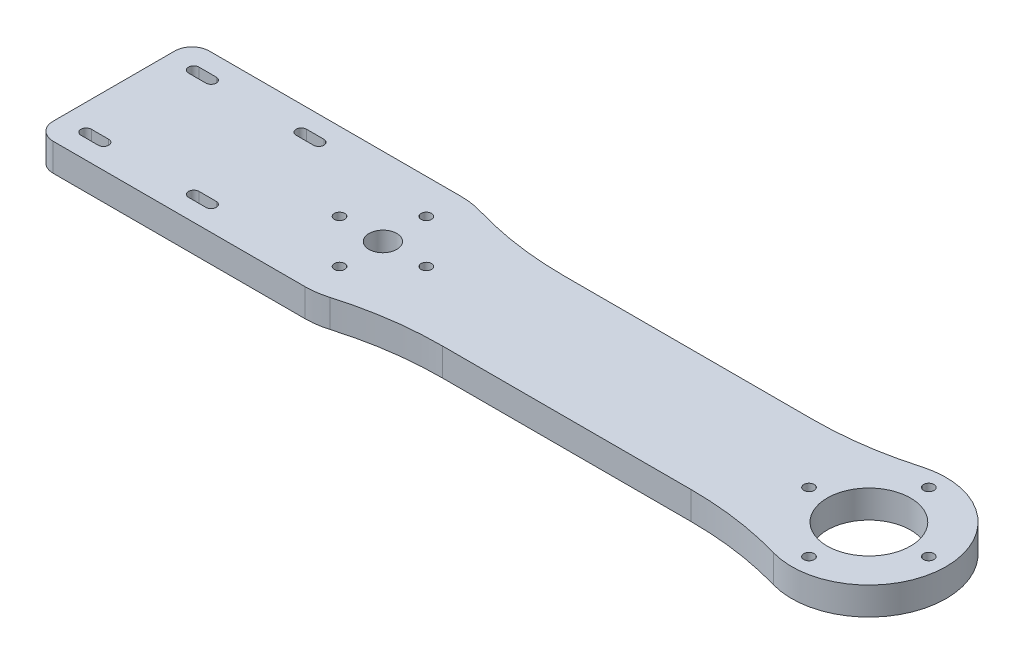
SolidWorks part; units mm, degrees
material "Pine"
ref_plane "Front Plane" through (0, 0, 0) normal (0, 0, 1) x (1, 0, 0)
ref_plane "Top Plane" through (0, 0, 0) normal (0, 1, 0) x (1, 0, 0)
ref_plane "Right Plane" through (0, 0, 0) normal (1, 0, 0) x (0, 0, -1)
sketch "Sketch1" plane through (0, 0, 0) normal (0, 1, 0) x (1, 0, 0)
  line L0 (0, 0) -> (140, 0) construction
  line L2 (0, 17.5) -> (140, 17.5)
  line L3 (0, -17.5) -> (140, -17.5)
  arc A0 (0, 17.5) -> (0, -17.5) centre (0, 0) ccw
  arc A1 (140, -17.5) -> (140, 17.5) centre (140, 0) ccw
  circle A2 centre (140, 0) radius 4
  circle A3 centre (0, 0) radius 4
  circle A4 centre (140, 0) radius 22.25
  circle A5 centre (0, 0) radius 20
  circle A6 centre (140, 0) radius 17.25
  point P5 (70, 0)
  dimension "D2" = 17.5
  dimension "D3" = 8
  dimension "D4" = 8
  dimension "D5" = 5
  dimension "D6" = 40
  dimension "D7" = 34.5
  dimension "D1" = 140
extrude "Boss-Extrude1" add sketch "Sketch1" along normal blind 8
sketch "Sketch2" plane through (0, 8, 0) normal (0, 1, 0) x (1, 0, 0)
  line L0 (0, 0) -> (-65, 0)
  line L1 (0, 0) -> (-65, 0) construction
  line L2 (0, -22.5) -> (-65, -22.5)
  line L3 (0, 22.5) -> (-65, 22.5)
  line L4 (-32.5, 0) -> (-65, 0)
  line L5 (-65, 0) -> (-65, 15.5)
  line L6 (-65, 15.5) -> (-70, 15.5) construction
  line L7 (-34, 15.5) -> (-39, 15.5) construction
  line L8 (-65, 14) -> (-70, 14)
  line L9 (-65, 17) -> (-70, 17)
  line L10 (-65, 22.5) -> (-77.5, 22.5)
  line L11 (-65, 22.5) -> (-65, -22.5)
  line L12 (-65, -22.5) -> (-77.5, -22.5)
  line L13 (-77.5, 22.5) -> (-77.5, -22.5)
  line L14 (-34, 14) -> (-39, 14)
  line L15 (-34, 17) -> (-39, 17)
  line L16 (-34, -15.5) -> (-39, -15.5) construction
  line L17 (-34, -17) -> (-39, -17)
  line L18 (-34, -14) -> (-39, -14)
  line L19 (-65, -15.5) -> (-70, -15.5) construction
  line L20 (-65, -17) -> (-70, -17)
  line L21 (-65, -14) -> (-70, -14)
  line L22 (-67.5, 15.5) -> (-36.5, -15.5)
  line L23 (-54.5, 0) -> (-49.5, 0) construction
  line L25 (-54.5, 11) -> (-49.5, 11)
  line L26 (-54.5, -11) -> (-49.5, -11)
  arc A0 (0, -22.5) -> (0, 22.5) centre (0, 0) ccw
  arc A1 (-65, 22.5) -> (-65, -22.5) centre (-65, 0) ccw
  circle A2 centre (0, 0) radius 4
  arc A3 (-65, 14) -> (-65, 17) centre (-65, 15.5) ccw
  arc A4 (-70, 17) -> (-70, 14) centre (-70, 15.5) ccw
  arc A5 (-34, 14) -> (-34, 17) centre (-34, 15.5) ccw
  arc A6 (-39, 17) -> (-39, 14) centre (-39, 15.5) ccw
  arc A7 (-34, -17) -> (-34, -14) centre (-34, -15.5) ccw
  arc A8 (-39, -14) -> (-39, -17) centre (-39, -15.5) ccw
  arc A9 (-65, -17) -> (-65, -14) centre (-65, -15.5) ccw
  arc A10 (-70, -14) -> (-70, -17) centre (-70, -15.5) ccw
  arc A11 (-54.5, 11) -> (-54.5, -11) centre (-54.5, 0) ccw
  arc A12 (-49.5, -11) -> (-49.5, 11) centre (-49.5, 0) ccw
  point P3 (-32.5, 0)
  point P16 (-67.5, 15.5)
  point P28 (-36.5, 15.5)
  point P35 (-36.5, -15.5)
  point P42 (-67.5, -15.5)
  point P50 (-52, 0)
  dimension "D2" = 22.5
  dimension "D3" = 65
  dimension "D1" = 65
  dimension "D4" = 12.5
  dimension "D5" = 2
  dimension "D7" = 0
  dimension "D6" = 2
extrude "Boss-Extrude2" add sketch "Sketch2" against normal blind 8
fillet "Fillet1" radius 5 2 edges at (-77.5, 4, 22.5) (-77.5, 4, -22.5)
sketch "Sketch3" plane through (0, 8, 0) normal (0, 1, 0) x (1, 0, 0)
  circle A0 centre (0, 0) radius 12.5
  circle A1 centre (0, 12.5) radius 1.5
  circle A2 centre (12.5, 0) radius 1.5
  circle A3 centre (0, -12.5) radius 1.5
  circle A4 centre (-12.5, 0) radius 1.5
  dimension "D1" = 25
  dimension "D2" = 3
  dimension "D3" = 4
extrude "Cut-Extrude1" cut sketch "Sketch3" against normal blind 19 contours A1 | A4 | A2 | A3
sketch "Sketch4" plane through (0, 8, 0) normal (0, 1, 0) x (1, 0, 0)
  circle A0 centre (140, 0) radius 17.25
  circle A3 centre (157.25, 0) radius 1.5
  circle A4 centre (140, -17.25) radius 1.5
  circle A5 centre (122.75, 0) radius 1.5
  circle A6 centre (140, 17.25) radius 1.5
  circle A7 centre (140, 0) radius 12
  dimension "D1" = 34.5
  dimension "D2" = 4
  dimension "D3" = 3
extrude "Cut-Extrude2" cut sketch "Sketch4" against normal blind 19 contours A3 | A6 | A5 | A4 | A7
fillet "Fillet2" radius 100 4 edges at (126.2591, 4, -17.5) (126.2591, 4, 17.5) (14.1421, 4, -17.5) (14.1421, 4, 17.5)
